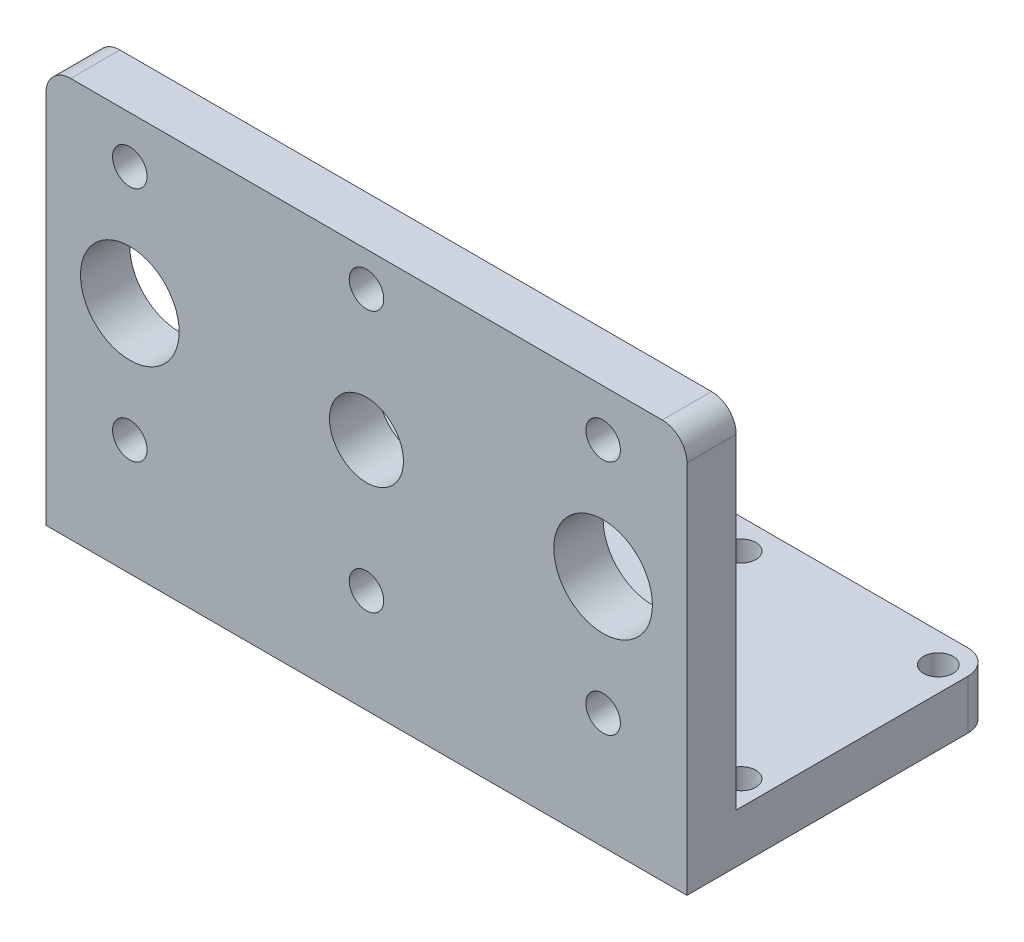
SolidWorks part; units mm, degrees
ref_plane "Front Plane" through (0, 0, 0) normal (0, 0, 1) x (1, 0, 0)
ref_plane "Top Plane" through (0, 0, 0) normal (0, 1, 0) x (1, 0, 0)
ref_plane "Right Plane" through (0, 0, 0) normal (1, 0, 0) x (0, 0, -1)
sketch "Sketch1" plane through (0, 0, 0) normal (0, 1, 0) x (1, 0, 0)
  line L0 (0, 0) -> (5, 0)
  line L1 (0, 0) -> (130, 0)
  line L2 (0, 0) -> (0, 63)
  line L3 (0, 63) -> (130, 63)
  line L4 (130, 0) -> (130, 63)
  line L5 (0, 0) -> (0, -37)
  line L6 (0, -37) -> (130, -37)
  line L7 (130, -37) -> (130, 0)
  line L9 (0, -37) -> (130, -37)
  line L10 (0, -37) -> (0, -27)
  line L11 (0, -27) -> (130, -27)
  line L12 (130, -37) -> (130, -27)
  circle A0 centre (5, 57) radius 3
  circle A1 centre (45, 57) radius 3
  circle A2 centre (5, 17) radius 3
  circle A3 centre (45, 17) radius 3
  circle A4 centre (85, 57) radius 3
  circle A5 centre (125, 57) radius 3
  circle A6 centre (85, 17) radius 3
  circle A7 centre (125, 17) radius 3
  dimension "D1" = 10
extrude "Boss-Extrude1" add sketch "Sketch1" along normal blind 10 contours L1 L4 L3 L2 L0 A7 A6 A5 A4 A3 A2 A1 A0 | L5 L11 L7 L1 L0 | L11 L5 L6 L7
sketch "Sketch2" plane through (0, 10, 0) normal (0, 1, 0) x (1, 0, 0)
  line L0 (130, -37) -> (130, 63) construction
  line L1 (0, -37) -> (130, -37)
  line L2 (0, -37) -> (0, -28.977)
  line L3 (0, -28.977) -> (130, -28.977)
  line L4 (130, -37) -> (130, -28.977)
extrude "Boss-Extrude2" add sketch "Sketch2" along normal blind 75
sketch "Sketch3" plane through (0, 0, 28.977) normal (0, 0, -1) x (-1, 0, 0)
  line L0 (-65, 47.5) -> (-65, 74)
  line L2 (-65, 10) -> (-65, 47.5)
  line L4 (-130, 10) -> (0, 10) construction
  line L5 (-65, 47.5) -> (-65, 21)
  line L6 (-65, 47.5) -> (-17, 47.5)
  line L7 (-17, 47.5) -> (-17, 71.4)
  line L8 (-17, 47.5) -> (-17, 23.6)
  line L9 (-65, 47.5) -> (-113, 47.5)
  line L10 (-113, 47.5) -> (-113, 71.4)
  line L11 (-113, 47.5) -> (-113, 23.6)
  circle A0 centre (-65, 21) radius 3.5
  circle A1 centre (-65, 74) radius 3.5
  circle A2 centre (-65, 47.5) radius 7.5
  circle A3 centre (-113, 71.4) radius 3.5
  circle A4 centre (-113, 23.6) radius 3.5
  circle A5 centre (-113, 47.5) radius 10
  circle A6 centre (-17, 47.5) radius 10
  circle A7 centre (-17, 71.4) radius 3.5
  circle A8 centre (-17, 23.6) radius 3.5
  dimension "D1" = 26.5
extrude "Cut-Extrude1" cut sketch "Sketch3" against normal blind 75
sketch "Sketch4" plane through (0, 0, 28.977) normal (0, 0, -1) x (-1, 0, 0)
  line L0 (-17, 71.4) -> (-17, 71.5)
  circle A0 centre (-17, 71.4) radius 3.5
  circle A1 centre (-17, 23.6) radius 3.5
  circle A2 centre (-113, 71.4) radius 3.5
  circle A3 centre (-113, 23.6) radius 3.5
extrude "Boss-Extrude3" add sketch "Sketch4" against normal blind 10
sketch "Sketch5" plane through (0, 0, 28.977) normal (0, 0, -1) x (-1, 0, 0)
  line L0 (-113, 47.5) -> (-113, 71.5)
  line L1 (-113, 47.5) -> (-113, 23.5)
  line L2 (-17, 47.5) -> (-17, 71.5)
  line L3 (-17, 47.5) -> (-17, 23.5)
  line L4 (-65, 47.5) -> (-65, 74)
  line L5 (-65, 47.5) -> (-65, 21)
  circle A0 centre (-113, 71.5) radius 3.5
  circle A1 centre (-17, 71.5) radius 3.5
  circle A2 centre (-17, 23.5) radius 3.5
  circle A3 centre (-113, 23.5) radius 3.5
  circle A4 centre (-65, 74) radius 3.5
  circle A5 centre (-65, 21) radius 3.5
extrude "Cut-Extrude2" cut sketch "Sketch5" against normal blind 10
sketch "Sketch7" plane through (0, 85, 0) normal (0, 1, 0) x (1, 0, 0)
  line L1 (0, -28.977) -> (130, -28.977)
  line L2 (0, -28.977) -> (0, -37)
  line L3 (0, -37) -> (130, -37)
  line L4 (130, -28.977) -> (130, -37)
extrude "Cut-Extrude3" cut sketch "Sketch7" against normal blind 4
fillet "Fillet2" radius 5 4 edges at (130, 5, -63) (0, 5, -63) (0, 81, 32.9885) (130, 81, 32.9885)
sketch "Sketch8" plane through (0, 0, 0) normal (-1, 0, 0) x (0, 0, 1)
  line L0 (37, 0) -> (37, 81)
  line L1 (37, 81) -> (41.6761, 81)
  line L2 (41.6761, 81) -> (41.6761, 0)
  line L3 (41.6761, 0) -> (37, 0)
extrude "Cut-Extrude4" cut sketch "Sketch8" against normal blind 500
sketch "Sketch9" plane through (0, 10, 0) normal (0, 1, 0) x (1, 0, 0)
  circle A0 centre (5, -23) radius 3
  circle A1 centre (45, -23) radius 3
  circle A2 centre (85, -23) radius 3
  circle A3 centre (125, -23) radius 3
extrude "Cut-Extrude5" cut sketch "Sketch9" against normal blind 500
sketch "Sketch11" plane through (0, 0, -63) normal (0, 0, -1) x (-1, 0, 0)
  line L1 (-130, 0) -> (0, 0)
  line L2 (-130, 0) -> (-130, 10)
  line L3 (-130, 10) -> (0, 10)
  line L4 (0, 0) -> (0, 10)
extrude "Cut-Extrude6" cut sketch "Sketch11" against normal blind 40
fillet "Fillet3" radius 5 1 edges at (0, 5, -23)
fillet "Fillet4" radius 5 1 edges at (130, 5, -23)
sketch "Sketch12" plane through (0, 0, 37) normal (0, 0, 1) x (1, 0, 0)
  line L0 (0, 81) -> (130, 81)
  line L1 (130, 81) -> (130, 0)
  line L2 (130, 0) -> (0, 0)
  line L3 (0, 0) -> (0, 81)
  circle A0 centre (17, 71.5) radius 3.5
  circle A1 centre (65, 74) radius 3.5
  circle A2 centre (113, 71.5) radius 3.5
  circle A3 centre (113, 47.5) radius 10
  circle A4 centre (65, 47.5) radius 7.5
  circle A5 centre (17, 47.5) radius 10
  circle A6 centre (17, 23.5) radius 3.5
  circle A7 centre (65, 21) radius 3.5
  circle A8 centre (113, 23.5) radius 3.5
  circle A9 centre (5, 76) radius 5
  circle A10 centre (125, 76) radius 5
  circle M1 centre (113, 71.5) radius 3.5
  circle M2 centre (113, 47.5) radius 10
  circle M3 centre (113, 23.5) radius 3.5
  circle M4 centre (65, 47.5) radius 7.5
  circle M5 centre (65, 21) radius 3.5
  circle M6 centre (65, 74) radius 3.5
  circle M7 centre (17, 47.5) radius 10
  circle M8 centre (17, 71.5) radius 3.5
  circle M9 centre (17, 23.5) radius 3.5
  line M10 (125, 81) -> (5, 81)
  arc M11 (5, 81) -> (0, 76) centre (5, 76) ccw
  line M12 (0, 76) -> (0, 0)
  line M13 (0, 0) -> (130, 0)
  line M14 (130, 0) -> (130, 76)
  arc M15 (130, 76) -> (125, 81) centre (125, 76) ccw
extrude "Boss-Extrude4" add sketch "Sketch12" along normal blind 1.98 contours A10 A9 M10 M12 M13 M14 M2 M4 M6 M8 M9 M7 M5 M3 M1 | A9 M11 | A10 M15
